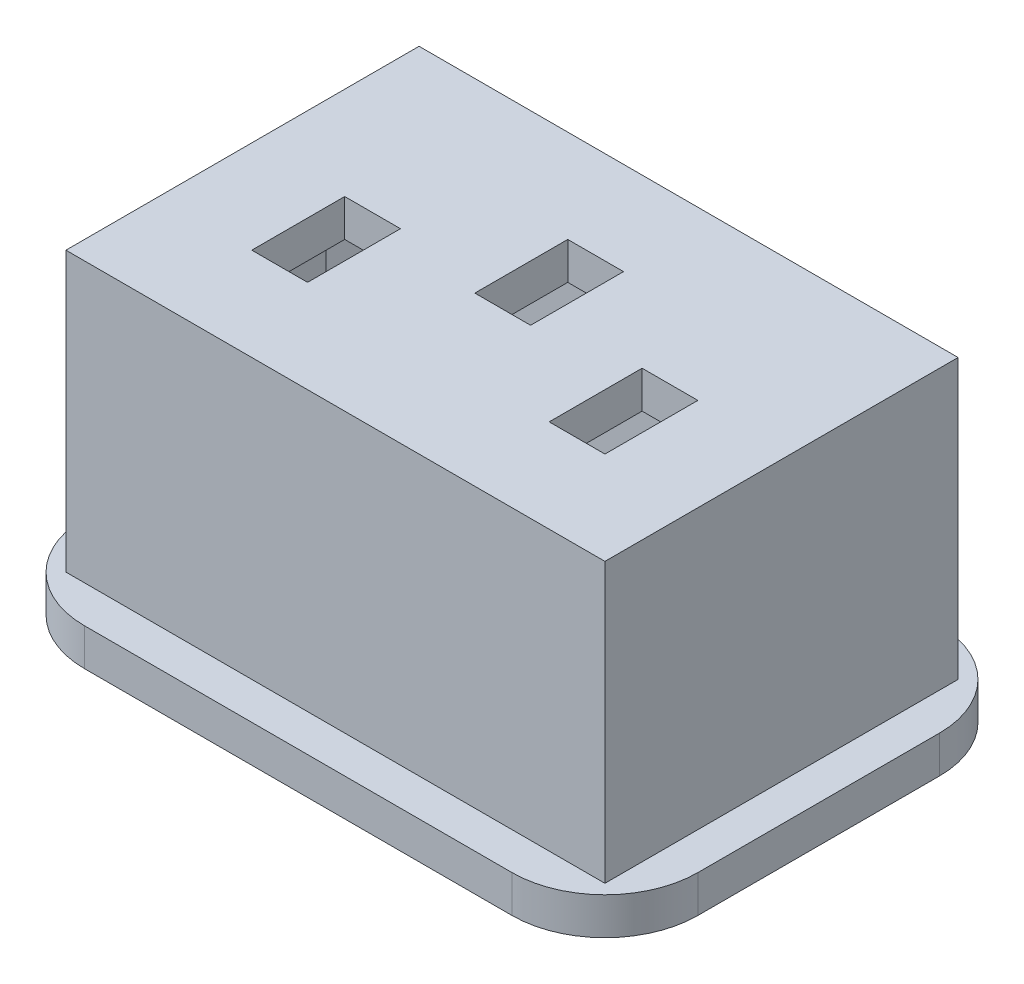
SolidWorks part; units mm, degrees
ref_plane "Front Plane" through (0, 0, 0) normal (0, 0, 1) x (1, 0, 0)
ref_plane "Top Plane" through (0, 0, 0) normal (0, 1, 0) x (1, 0, 0)
ref_plane "Right Plane" through (0, 0, 0) normal (1, 0, 0) x (0, 0, -1)
sketch "Sketch1" plane through (0, 0, 0) normal (0, 1, 0) x (1, 0, 0)
  line L0 (0, 0) -> (25, 0)
  line L1 (25, 0) -> (25, 10)
  line L2 (0, 0) -> (0, 10)
  line L3 (5, 15) -> (20, 15)
  line L4 (0, 10) -> (5, 15)
  line L5 (20, 15) -> (25, 10)
  line L6 (-2, -2) -> (27, -2)
  line L7 (-2, -2) -> (-2, 17)
  line L8 (3, 3) -> (6, 3)
  line L9 (3, 3) -> (3, 8)
  line L10 (3, 8) -> (6, 8)
  line L11 (6, 3) -> (6, 8)
  line L12 (22, 3) -> (19, 3)
  line L13 (22, 3) -> (22, 8)
  line L14 (22, 8) -> (19, 8)
  line L15 (19, 3) -> (19, 8)
  line L16 (11, 12) -> (14, 12)
  line L17 (11, 12) -> (11, 7)
  line L18 (11, 7) -> (14, 7)
  line L19 (14, 12) -> (14, 7)
  line L20 (-2, 17) -> (27, 17)
  line L21 (27, 17) -> (27, -2)
  point P7 (12.5, 15)
  point P8 (12.5, 0)
  point P23 (12.5, 7)
  dimension "D1" = 25
  dimension "D2" = 10
  dimension "D3" = 15
  dimension "D4" = 15
  dimension "D5" = 0
  dimension "D6" = 2
  dimension "D7" = 2
  dimension "D8" = 2
  dimension "D9" = 3
  dimension "D10" = 3
  dimension "D11" = 5
  dimension "D12" = 3
  dimension "D13" = 3
  dimension "D14" = 3
  dimension "D15" = 0
  dimension "D16" = 3
  dimension "D17" = 5
  dimension "D18" = 3
  dimension "D19" = 2
sketch "Sketch2" plane through (0, 0, 0) normal (0, 1, 0) x (1, 0, 0)
  line L1 (-2, -2) -> (27, -2)
  line L2 (-2, -2) -> (-2, 17)
  line L3 (-2, 17) -> (27, 17)
  line L4 (27, -2) -> (27, 17)
extrude "Boss-Extrude1" add sketch "Sketch2" along normal blind 15
sketch "Sketch3" plane through (0, 0, 0) normal (0, -1, 0) x (1, 0, 0)
  line L0 (0, 0) -> (0, -10)
  line L1 (0, -10) -> (5, -15)
  line L2 (5, -15) -> (20, -15)
  line L3 (20, -15) -> (25, -10)
  line L4 (25, -10) -> (25, 0)
  line L5 (25, 0) -> (0, 0)
extrude "Cut-Extrude1" cut sketch "Sketch3" against normal blind 13
sketch "Sketch4" plane through (0, 13, 0) normal (0, -1, 0) x (1, 0, 0)
  line L1 (3, -3) -> (6, -3)
  line L2 (3, -3) -> (3, -8)
  line L3 (3, -8) -> (6, -8)
  line L4 (6, -3) -> (6, -8)
  line L5 (11, -7) -> (14, -7)
  line L6 (11, -7) -> (11, -12)
  line L7 (11, -12) -> (14, -12)
  line L8 (14, -7) -> (14, -12)
  line L9 (19, -3) -> (22, -3)
  line L10 (19, -3) -> (19, -8)
  line L11 (19, -8) -> (22, -8)
  line L12 (22, -3) -> (22, -8)
extrude "Cut-Extrude2" cut sketch "Sketch4" against normal blind 13
sketch "Sketch5" plane through (0, 0, 0) normal (0, -1, 0) x (1, 0, 0)
  line L1 (-4, 4) -> (29, 4)
  line L2 (-4, 4) -> (-4, -19)
  line L3 (-4, -19) -> (29, -19)
  line L4 (29, 4) -> (29, -19)
  line L5 (0, 0) -> (0, -10)
  line L6 (0, -10) -> (5, -15)
  line L7 (5, -15) -> (20, -15)
  line L8 (20, -15) -> (25, -10)
  line L9 (25, -10) -> (25, 0)
  line L10 (25, 0) -> (0, 0)
  dimension "D1" = 2
  dimension "D2" = 2
  dimension "D3" = 2
  dimension "D4" = 2
extrude "Boss-Extrude2" add sketch "Sketch5" along normal blind 2
fillet "Fillet1" radius 5 1 edges at (29, -1, -19)
fillet "Fillet2" radius 5 1 edges at (29, -1, 4)
fillet "Fillet3" radius 5 1 edges at (-4, -1, 4)
fillet "Fillet4" radius 5 1 edges at (-4, -1, -19)
